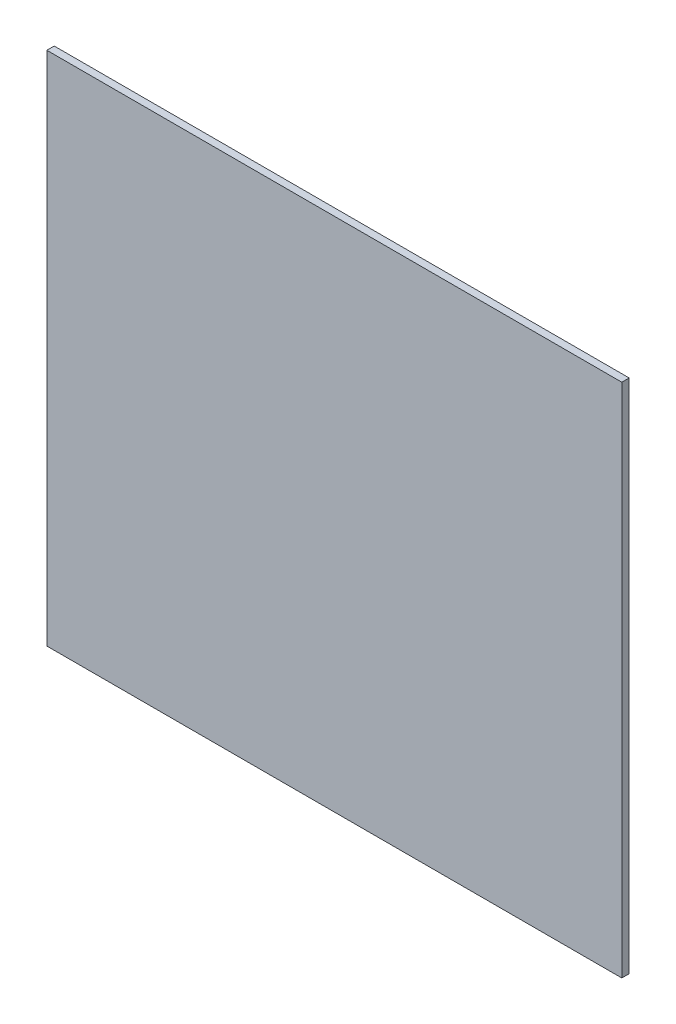
SolidWorks part; units mm, degrees
ref_plane "Front" through (0, 0, 0) normal (0, 0, 1) x (1, 0, 0)
ref_plane "Top" through (0, 0, 0) normal (0, 1, 0) x (1, 0, 0)
ref_plane "Right" through (0, 0, 0) normal (1, 0, 0) x (0, 0, -1)
sketch "Sketch1" plane through (0, 0, 0) normal (0, 0, 1) x (1, 0, 0)
  line L5 (-49.2125, 55.5625) -> (74.6125, 55.5625)
  line L6 (-49.2125, 55.5625) -> (-49.2125, -55.5625)
  line L7 (-49.2125, -55.5625) -> (74.6125, -55.5625)
  line L8 (74.6125, 55.5625) -> (74.6125, -55.5625)
extrude "Extrude1" add sketch "Sketch1" along normal blind 1.5875
